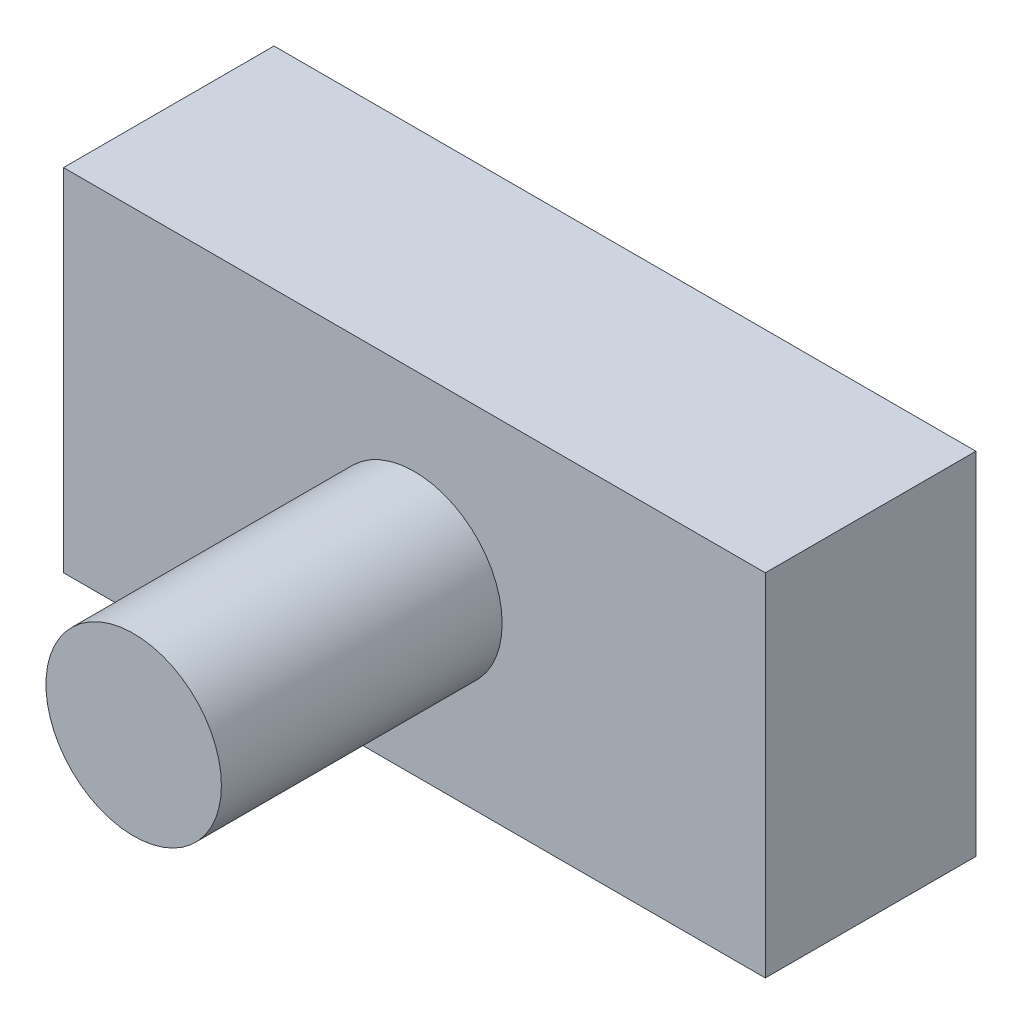
SolidWorks part; units mm, degrees
ref_plane "Front Plane" through (0, 0, 0) normal (0, 0, 1) x (1, 0, 0)
ref_plane "Top Plane" through (0, 0, 0) normal (0, 1, 0) x (1, 0, 0)
ref_plane "Right Plane" through (0, 0, 0) normal (1, 0, 0) x (0, 0, -1)
sketch "Sketch1" plane through (0, 0, 0) normal (0, 0, 1) x (1, 0, 0)
  line L1 (0, 0) -> (200, 0)
  line L2 (0, 0) -> (0, 100)
  line L3 (0, 100) -> (200, 100)
  line L4 (200, 0) -> (200, 100)
  dimension "D1" = 200
  dimension "D2" = 100
extrude "Boss-Extrude1" add sketch "Sketch1" along normal blind 60
sketch "Sketch2" plane through (0, 0, 60) normal (0, 0, 1) x (1, 0, 0)
  line L0 (0, 100) -> (0, 0) construction
  line L1 (200, 100) -> (0, 100) construction
  circle A0 centre (100, 50) radius 25
  dimension "D1" = 50
  dimension "D2" = 100
  dimension "D3" = 50
extrude "Boss-Extrude2" add sketch "Sketch2" along normal blind 80
